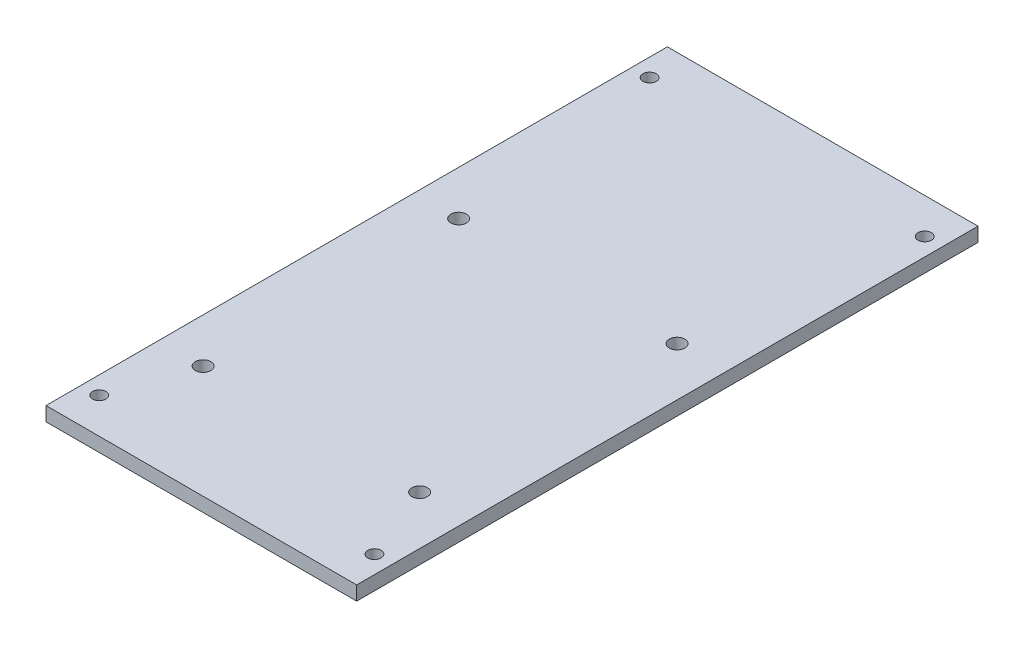
SolidWorks part; units mm, degrees
ref_plane "Front Plane" through (0, 0, 0) normal (0, 0, 1) x (1, 0, 0)
ref_plane "Top Plane" through (0, 0, 0) normal (0, 1, 0) x (1, 0, 0)
ref_plane "Right Plane" through (0, 0, 0) normal (1, 0, 0) x (0, 0, -1)
sketch "Sketch2" plane through (0, 0, 0) normal (0, 1, 0) x (1, 0, 0)
  line L0 (0, 70) -> (0, -70) construction
  line L1 (35, -70) -> (-35, -70)
  line L2 (35, -70) -> (35, 70)
  line L3 (35, 70) -> (-35, 70)
  line L4 (-35, -70) -> (-35, 70)
  line L5 (35, -70) -> (-35, 70) construction
  line L6 (35, 70) -> (-35, -70) construction
  line L7 (35, 0) -> (-35, 0) construction
  circle A0 centre (31, -62) radius 1.5
  circle A1 centre (31, 62) radius 1.5
  circle A2 centre (-31, 62) radius 1.5
  circle A3 centre (-31, -62) radius 1.5
  point P0 (0, 0)
  dimension "D4" = 3
  dimension "D1" = 70
  dimension "D2" = 140
  dimension "D3" = 4
  dimension "D5" = 8
extrude "Boss-Extrude1" add sketch "Sketch2" along normal blind 3.175
sketch "Sketch3" plane through (0, 3.175, 0) normal (0, 1, 0) x (1, 0, 0)
  line L0 (-35, -15.8101) -> (35, -15.8101) construction
  line L1 (-35, 70) -> (-35, -70) construction
  line L2 (35, -70) -> (35, 70) construction
  circle A0 centre (-24.9995, -44.6) radius 1.75
  circle A1 centre (24, -44.8101) radius 1.75
  circle A2 centre (24, 13.1899) radius 1.75
  circle A3 centre (-24.9995, 12.9799) radius 1.75
  dimension "D1" = 49
  dimension "D2" = 25.4
  dimension "D3" = 11
  dimension "D4" = 29
extrude "Cut-Extrude1" cut sketch "Sketch3" against normal through all
